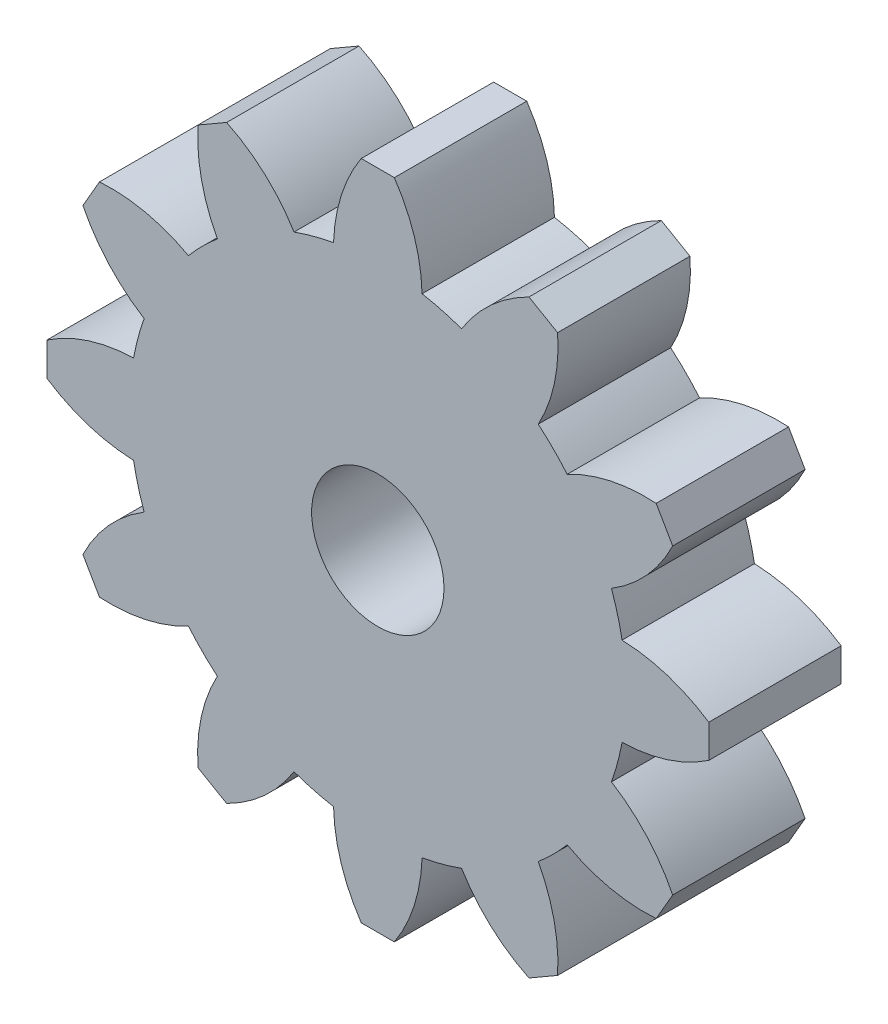
SolidWorks part; units mm, degrees
ref_plane "Front Plane" through (0, 0, 0) normal (1, 0, 0) x (0, 1, 0)
ref_plane "Top Plane" through (0, 0, 0) normal (0, 0, 1) x (0, 1, 0)
ref_plane "Right Plane" through (0, 0, 0) normal (0, 1, 0) x (-1, 0, 0)
sketch "Sketch1" plane through (0, 0, 0) normal (0, 0, 1) x (0, 1, 0)
  line L0 (-23.9177, 0) -> (22.2962, 0) construction
  line L1 (14.7596, 2.675) -> (14.7596, -2.675) construction
  line L2 (20, 1) -> (20, -1)
  line L3 (17.8205, -9.134) -> (16.8205, -10.866)
  line L4 (10.866, -16.8205) -> (9.134, -17.8205)
  line L5 (1, -20) -> (-1, -20)
  line L6 (-9.134, -17.8205) -> (-10.866, -16.8205)
  line L7 (-16.8205, -10.866) -> (-17.8205, -9.134)
  line L8 (-20, -1) -> (-20, 1)
  line L9 (-17.8205, 9.134) -> (-16.8205, 10.866)
  line L10 (-10.866, 16.8205) -> (-9.134, 17.8205)
  line L11 (-1, 20) -> (1, 20)
  line L12 (9.134, 17.8205) -> (10.866, 16.8205)
  line L13 (16.8205, 10.866) -> (17.8205, 9.134)
  arc A0 (14.7596, 2.675) -> (14.1196, 5.0632) centre (0, 0) ccw
  circle A1 centre (0, 0) radius 4
  arc A4 (14.7596, -2.675) -> (20, -1) centre (14.5326, 7.0703) ccw
  arc A5 (20, 1) -> (14.7596, 2.675) centre (14.4221, -7.416) ccw
  arc A6 (17.8205, -9.134) -> (14.1196, -5.0632) centre (8.7819, -13.6335) ccw
  arc A7 (11.4446, -9.6964) -> (16.8205, -10.866) centre (16.1207, -1.1432) ccw
  arc A8 (10.866, -16.8205) -> (9.6964, -11.4446) centre (0.7886, -16.1979) ccw
  arc A9 (5.0632, -14.1196) -> (9.134, -17.8205) centre (13.3894, -9.0504) ccw
  arc A10 (1, -20) -> (2.675, -14.7596) centre (-7.416, -14.4221) ccw
  arc A11 (-2.675, -14.7596) -> (-1, -20) centre (7.0703, -14.5326) ccw
  arc A12 (-9.134, -17.8205) -> (-5.0632, -14.1196) centre (-13.6335, -8.7819) ccw
  arc A13 (-9.6964, -11.4446) -> (-10.866, -16.8205) centre (-1.1432, -16.1207) ccw
  arc A14 (-16.8205, -10.866) -> (-11.4446, -9.6964) centre (-16.1979, -0.7886) ccw
  arc A15 (-14.1196, -5.0632) -> (-17.8205, -9.134) centre (-9.0504, -13.3894) ccw
  arc A16 (-20, -1) -> (-14.7596, -2.675) centre (-14.4221, 7.416) ccw
  arc A17 (-14.7596, 2.675) -> (-20, 1) centre (-14.5326, -7.0703) ccw
  arc A18 (-17.8205, 9.134) -> (-14.1196, 5.0632) centre (-8.7819, 13.6335) ccw
  arc A19 (-11.4446, 9.6964) -> (-16.8205, 10.866) centre (-16.1207, 1.1432) ccw
  arc A20 (-10.866, 16.8205) -> (-9.6964, 11.4446) centre (-0.7886, 16.1979) ccw
  arc A21 (-5.0632, 14.1196) -> (-9.134, 17.8205) centre (-13.3894, 9.0504) ccw
  arc A22 (-1, 20) -> (-2.675, 14.7596) centre (7.416, 14.4221) ccw
  arc A23 (2.675, 14.7596) -> (1, 20) centre (-7.0703, 14.5326) ccw
  arc A24 (9.134, 17.8205) -> (5.0632, 14.1196) centre (13.6335, 8.7819) ccw
  arc A25 (9.6964, 11.4446) -> (10.866, 16.8205) centre (1.1432, 16.1207) ccw
  arc A26 (16.8205, 10.866) -> (11.4446, 9.6964) centre (16.1979, 0.7886) ccw
  arc A27 (14.1196, 5.0632) -> (17.8205, 9.134) centre (9.0504, 13.3894) ccw
  arc A28 (14.7596, 2.675) -> (14.1196, 5.0632) centre (0, 0) ccw
  arc A29 (14.1196, -5.0632) -> (14.7596, -2.675) centre (0, 0) ccw
  arc A30 (9.6964, -11.4446) -> (11.4446, -9.6964) centre (0, 0) ccw
  arc A31 (2.675, -14.7596) -> (5.0632, -14.1196) centre (0, 0) ccw
  arc A32 (-5.0632, -14.1196) -> (-2.675, -14.7596) centre (0, 0) ccw
  arc A33 (-11.4446, -9.6964) -> (-9.6964, -11.4446) centre (0, 0) ccw
  arc A34 (-14.7596, -2.675) -> (-14.1196, -5.0632) centre (0, 0) ccw
  arc A35 (-14.1196, 5.0632) -> (-14.7596, 2.675) centre (0, 0) ccw
  arc A36 (-9.6964, 11.4446) -> (-11.4446, 9.6964) centre (0, 0) ccw
  arc A37 (-2.675, 14.7596) -> (-5.0632, 14.1196) centre (0, 0) ccw
  arc A38 (5.0632, 14.1196) -> (2.675, 14.7596) centre (0, 0) ccw
  arc A39 (11.4446, 9.6964) -> (9.6964, 11.4446) centre (0, 0) ccw
  point P81 (0, 0)
  dimension "D1" = 8
  dimension "D2" = 30
  dimension "D7" = 5.35
  dimension "D6" = 9.748
  dimension "D9" = 10.0966
  dimension "D3" = 20
  dimension "D4" = 1
  dimension "D5" = 1
  dimension "D8" = 12
extrude "Boss-Extrude1" add sketch "Sketch1" along normal blind 8 contours A26 A39 A25 L12 A24 A38 A23 L11 A22 A37 A21 L10 A20 A36 A19 L9 A18 A35 A17 L8 A16 A34 A15 L7 A14 A33 A13 L6 A12 A32 A11 L5 A10 A31 A9 L4 A8 A30 A7 L3 A6 A29 A4 L2 A5 A0 A27 L13 A1
